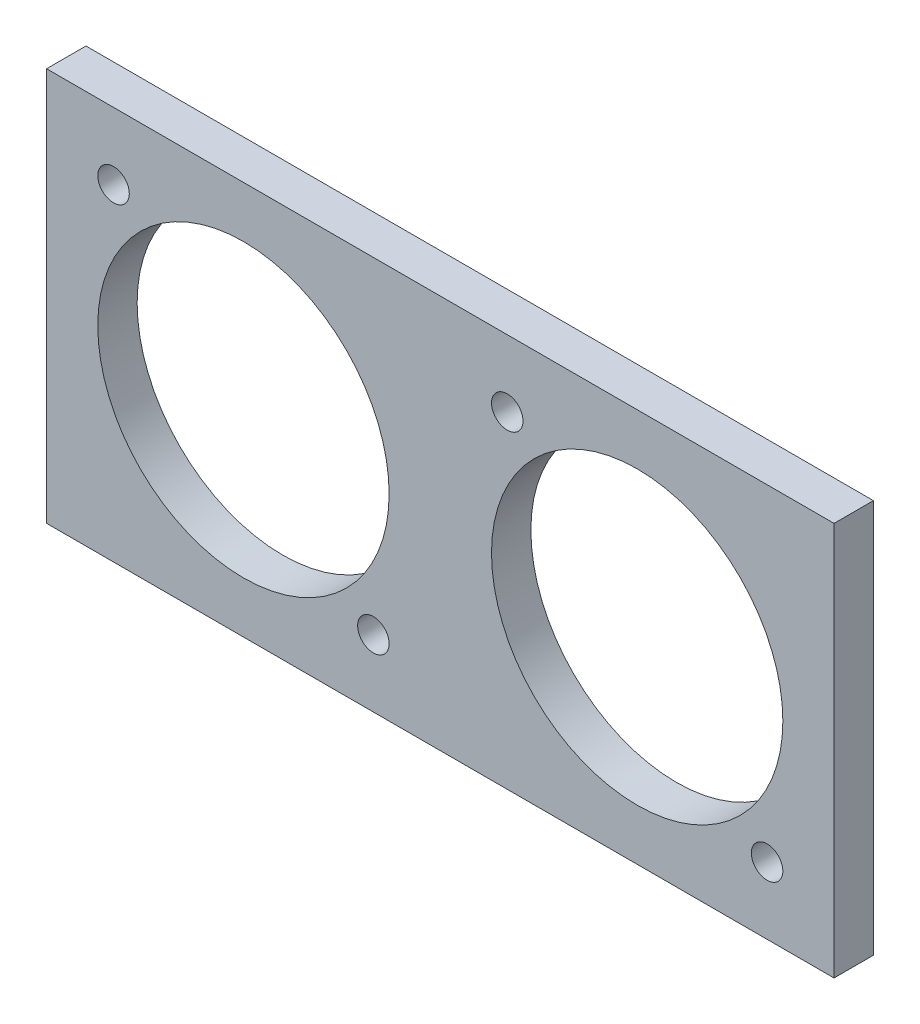
SolidWorks part; units mm, degrees
ref_plane "Plan de face" through (0, 0, 0) normal (0, 0, 1) x (1, 0, 0)
ref_plane "Plan de dessus" through (0, 0, 0) normal (0, 1, 0) x (1, 0, 0)
ref_plane "Plan de droite" through (0, 0, 0) normal (1, 0, 0) x (0, 0, -1)
sketch "Esquisse1" plane through (0, 0, 0) normal (0, 0, 1) x (1, 0, 0)
  line L1 (0, 0) -> (60, 0)
  line L2 (0, 0) -> (0, 30)
  line L3 (0, 30) -> (60, 30)
  line L4 (60, 0) -> (60, 30)
  dimension "D1" = 60
  dimension "D2" = 30
extrude "Boss.-Extru.1" add sketch "Esquisse1" along normal blind 3
sketch "Esquisse2" plane through (0, 0, 3) normal (0, 0, 1) x (1, 0, 0)
  line L0 (0, 15) -> (15, 15) construction
  line L1 (0, 30) -> (0, 0) construction
  line L2 (15, 15) -> (45, 15) construction
  line L3 (45, 15) -> (60, 15) construction
  line L4 (60, 0) -> (60, 30) construction
  line L5 (5.1005, 24.8995) -> (24.8995, 5.1005) construction
  line L6 (35.1005, 24.8995) -> (54.8995, 5.1005) construction
  circle A0 centre (15, 15) radius 11.1
  circle A1 centre (45, 15) radius 11.1
  circle A2 centre (5.1005, 24.8995) radius 1.2
  circle A3 centre (24.8995, 5.1005) radius 1.2
  circle A4 centre (15, 15) radius 14 construction
  circle A5 centre (45, 15) radius 14 construction
  circle A6 centre (35.1005, 24.8995) radius 1.2
  circle A7 centre (54.8995, 5.1005) radius 1.2
  point P20 (0, 0)
  dimension "D1" = 22.2
  dimension "D2" = 22.2
  dimension "D4" = 2.4
  dimension "D3" = 45
  dimension "D5" = 30
  dimension "D6" = 28
extrude "Enlèv. mat.-Extru.1" cut sketch "Esquisse2" against normal through all
